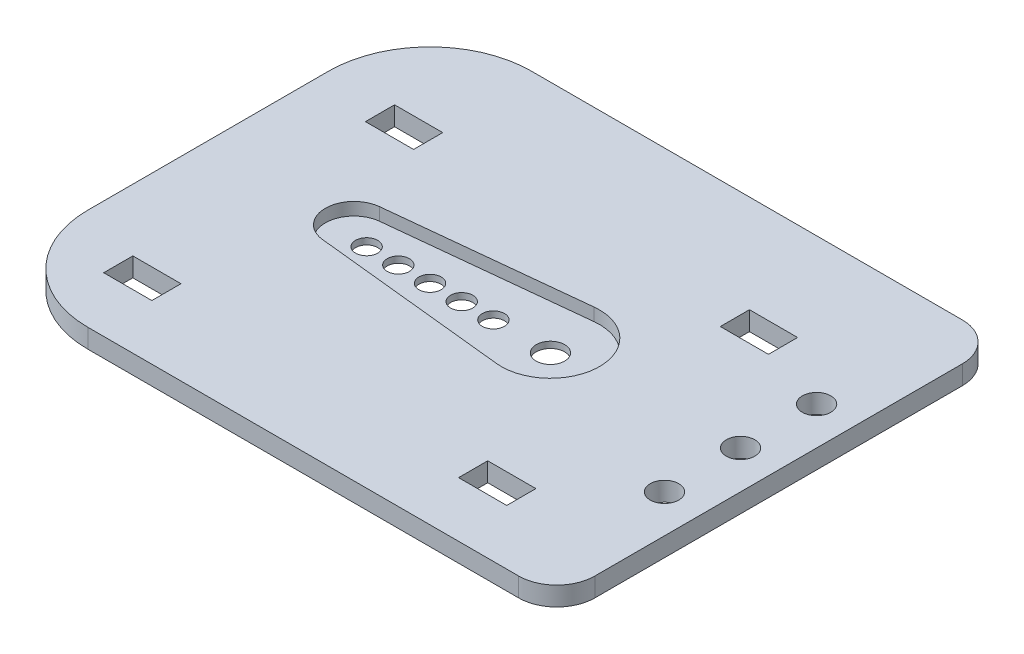
SolidWorks part; units mm, degrees
ref_plane "Front" through (0, 0, 0) normal (0, 0, 1) x (1, 0, 0)
ref_plane "Top" through (0, 0, 0) normal (0, 1, 0) x (1, 0, 0)
ref_plane "Right" through (0, 0, 0) normal (1, 0, 0) x (0, 0, -1)
sketch "Croquis1" plane through (0, 0, 0) normal (0, 1, 0) x (1, 0, 0)
  line L0 (-313.7799, 0) -> (15375.2154, 0) construction
  line L1 (0, -313.7799) -> (0, 15375.2154) construction
  line L3 (-14.5, -17.5) -> (19.5, -17.5)
  line L4 (-22.5, -9.5) -> (-22.5, 9.5)
  line L5 (-14.5, 17.5) -> (19.5, 17.5)
  line L6 (22.5, -14.5) -> (22.5, 14.5)
  line L7 (-22.5, -17.5) -> (22.5, 17.5) construction
  line L8 (-22.5, 17.5) -> (22.5, -17.5) construction
  arc A0 (-14.5, 17.5) -> (-22.5, 9.5) centre (-14.5, 9.5) ccw
  arc A1 (-14.5, -17.5) -> (-22.5, -9.5) centre (-14.5, -9.5) cw
  arc A2 (22.5, 14.5) -> (19.5, 17.5) centre (19.5, 14.5) ccw
  arc A3 (19.5, -17.5) -> (22.5, -14.5) centre (19.5, -14.5) ccw
  point P4 (0, 0)
  dimension "D3" = 8
  dimension "D4" = 8
  dimension "D5" = 3
  dimension "D6" = 3
  dimension "D1" = 45
  dimension "D2" = 35
extrude "Saliente-Extruir1" add sketch "Croquis1" along normal blind 1.5
sketch "Croquis2" plane through (0, 1.5, 0) normal (0, 1, 0) x (1, 0, 0)
  line L0 (-1000, 0) -> (49000, 0) construction
  line L1 (0, -1000) -> (0, 49000) construction
  line L2 (-11.2355, 2.2477) -> (4.0963, 3.8539)
  line L3 (-11.2355, -2.2477) -> (4.0963, -3.8539)
  line L4 (22.5, -14.5) -> (22.5, 14.5) construction
  arc A0 (4.0963, -3.8539) -> (4.0963, 3.8539) centre (4.5, 0) ccw
  arc A1 (-11.2355, 2.2477) -> (-11.2355, -2.2477) centre (-11, 0) ccw
  dimension "D1" = 4.52
  dimension "D2" = 7.75
  dimension "D3" = 15.5
  dimension "D4" = 18
extrude "Cortar-Extruir1" cut sketch "Croquis2" against normal blind 1
sketch "Croquis3" plane through (0, 0.5, 0) normal (0, 1, 0) x (1, 0, 0)
  line L0 (-991.9304, 0) -> (49008.0696, 0) construction
  line L1 (4.5, -1000) -> (4.5, 49000) construction
  line L2 (19.5, -1000) -> (19.5, 49000) construction
  line L3 (-991.9304, -6) -> (49008.0696, -6) construction
  line L4 (-991.9304, 6) -> (49008.0696, 6) construction
  line L5 (-13.7972, 7.5) -> (-13.7972, 9.8)
  line L6 (-991.9304, -12) -> (49008.0696, -12) construction
  line L7 (-991.9304, 12) -> (49008.0696, 12) construction
  line L8 (-15.6972, -1012) -> (-15.6972, 48988) construction
  line L9 (-17.5972, -13.15) -> (-13.7972, -13.15)
  line L10 (-17.5972, -13.15) -> (-17.5972, -10.85)
  line L11 (-17.5972, -10.85) -> (-13.7972, -10.85)
  line L12 (-13.7972, -13.15) -> (-13.7972, -10.85)
  line L13 (-17.5972, -13.15) -> (-13.7972, -10.85) construction
  line L14 (-17.5972, -10.85) -> (-13.7972, -13.15) construction
  line L15 (-1.6972, -1012) -> (-1.6972, 48988) construction
  line L16 (14.2028, -13.15) -> (14.2028, -10.85)
  line L17 (14.2028, -13.15) -> (10.4028, -13.15)
  line L18 (10.4028, -13.15) -> (10.4028, -10.85)
  line L19 (14.2028, -10.85) -> (10.4028, -10.85)
  line L20 (10.4028, 13.15) -> (10.4028, 10.85) construction
  line L21 (14.2028, 13.15) -> (10.4028, 13.15) construction
  line L22 (14.2028, 13.15) -> (14.2028, 10.85) construction
  line L23 (14.2028, 10.85) -> (10.4028, 10.85) construction
  line L24 (-17.5972, 13.15) -> (-17.5972, 10.85) construction
  line L25 (-17.5972, 13.15) -> (-13.7972, 13.15) construction
  line L26 (-13.7972, 13.15) -> (-13.7972, 10.85) construction
  line L27 (-17.5972, 10.85) -> (-13.7972, 10.85) construction
  line L28 (14.2028, 7.5) -> (10.4028, 7.5)
  line L29 (-17.5972, 7.5) -> (-17.5972, 9.8)
  line L30 (14.2028, 7.5) -> (14.2028, 9.8)
  line L31 (-17.5972, 9.8) -> (-13.7972, 9.8)
  line L32 (-17.5972, 7.5) -> (-13.7972, 7.5)
  line L33 (10.4028, 7.5) -> (10.4028, 9.8)
  line L34 (14.2028, 9.8) -> (10.4028, 9.8)
  circle A0 centre (4.5, 0) radius 1.125
  circle A1 centre (19.5, 6) radius 1.125
  circle A2 centre (19.5, -6) radius 1.125
  circle A3 centre (19.5, 0) radius 1.125
  point P23 (-15.6972, -12)
  dimension "D1" = 2.25
  dimension "D5" = 2.25
  dimension "D6" = 6
  dimension "D7" = 2.25
  dimension "D8" = 12
  dimension "D12" = 20.1972
  dimension "D2" = 15
  dimension "D10" = 3.8
  dimension "D11" = 14
  dimension "D9" = 2.3
  dimension "D4" = 12
  dimension "D13" = 3.8
  dimension "D14" = 2.3
  dimension "D15" = 7.5
  dimension "D16" = 12.1
  dimension "D17" = 3.8
  dimension "D18" = 2.3
  dimension "D19" = 7.5
  dimension "D20" = 12.1
  dimension "D21" = 2.3
  dimension "D22" = 2.3
  dimension "D3" = 6
extrude "Cortar-Extruir2" cut sketch "Croquis3" against normal mid plane 2
fillet "Redondeo1" [suppressed] radius 1
sketch "Croquis4" plane through (0, 1.5, 0) normal (0, 1, 0) x (1, 0, 0)
  line L0 (-1000, 0) -> (49000, 0) construction
  line L1 (0, -1000) -> (0, 49000) construction
  line L2 (-1.25, -1000) -> (-1.25, 49000) construction
  line L3 (-2.5, -1000) -> (-2.5, 49000) construction
  line L4 (-3.75, -1000) -> (-3.75, 49000) construction
  line L5 (-5, -1000) -> (-5, 49000) construction
  line L6 (-6.25, -1000) -> (-6.25, 49000) construction
  line L7 (-7.5, -1000) -> (-7.5, 49000) construction
  line L8 (-8.75, -1000) -> (-8.75, 49000) construction
  line L9 (-10, -1000) -> (-10, 49000) construction
  circle A0 centre (0, 0) radius 0.875
  circle A1 centre (-5, 0) radius 0.875
  circle A2 centre (-2.5, 0) radius 0.875
  circle A3 centre (-7.5, 0) radius 0.875
  circle A4 centre (-10, 0) radius 0.875
  dimension "D1" = 1.75
  dimension "D2" = 1.25
  dimension "D3" = 1.25
  dimension "D4" = 1.25
  dimension "D5" = 1.25
  dimension "D6" = 1.25
  dimension "D7" = 1.25
  dimension "D8" = 1.25
  dimension "D9" = 1.25
extrude "Cortar-Extruir3" cut sketch "Croquis4" against normal blind 10
